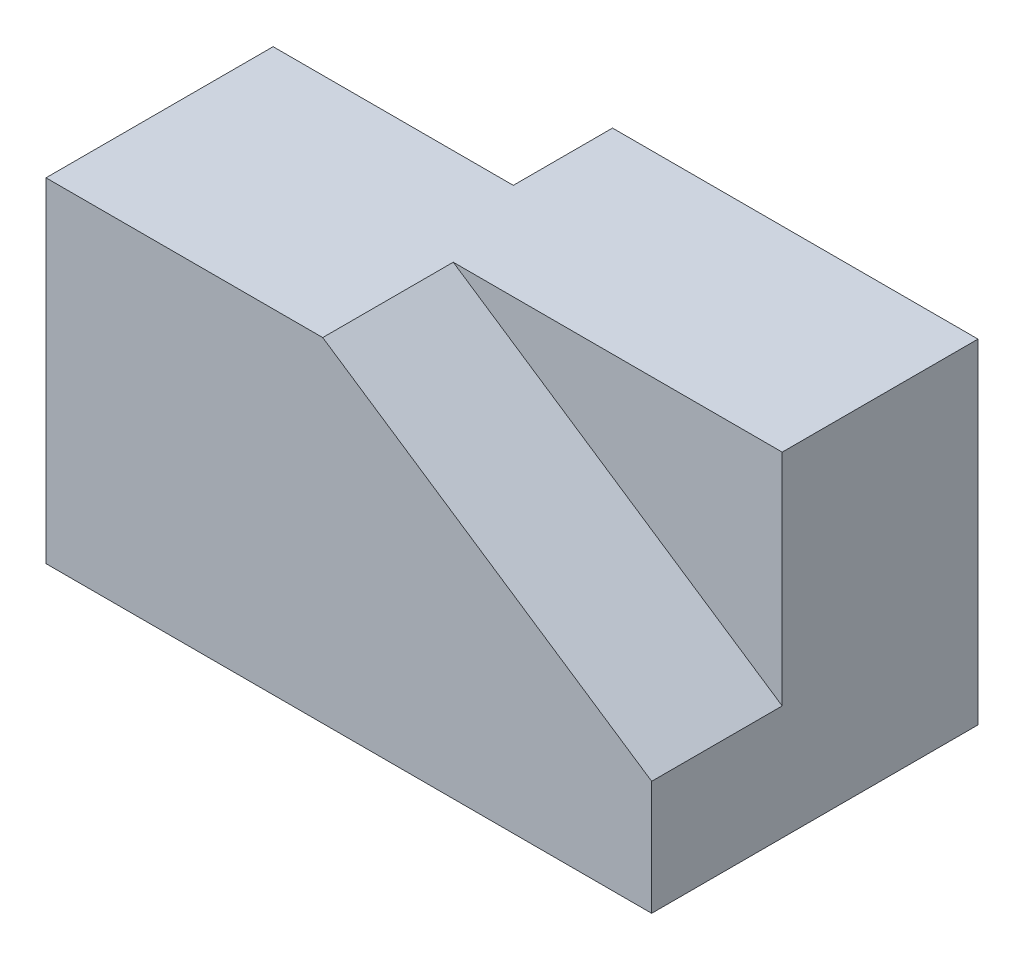
SolidWorks part; units mm, degrees
ref_plane "Front Plane" through (0, 0, 0) normal (0, 0, 1) x (1, 0, 0)
ref_plane "Top Plane" through (0, 0, 0) normal (0, 1, 0) x (1, 0, 0)
ref_plane "Right Plane" through (0, 0, 0) normal (1, 0, 0) x (0, 0, -1)
sketch "Sketch1" plane through (0, 0, 0) normal (0, 1, 0) x (1, 0, 0)
  line L1 (0, 0) -> (58.928, 0)
  line L2 (0, 0) -> (0, 31.75)
  line L3 (0, 31.75) -> (58.928, 31.75)
  line L4 (58.928, 0) -> (58.928, 31.75)
  dimension "D1" = 58.928
  dimension "D2" = 31.75
extrude "Boss-Extrude1" add sketch "Sketch1" along normal blind 32.512
sketch "Sketch3" plane through (0, 0, 0) normal (0, 0, 1) x (1, 0, 0)
  line L0 (26.924, 32.512) -> (58.928, 11.1252)
  line L1 (0, 32.512) -> (58.928, 32.512) construction
  line L3 (58.928, 11.1252) -> (58.928, 32.512)
  line L4 (58.928, 32.512) -> (26.924, 32.512)
  line L5 (0, 32.512) -> (26.924, 32.512) construction
  line L6 (58.928, 11.1252) -> (58.928, 0) construction
  line L7 (58.928, 32.512) -> (58.928, 0) construction
  dimension "D1" = 26.924
  dimension "D2" = 11.1252
extrude "Cut-Extrude1" cut sketch "Sketch3" against normal blind 12.7
sketch "Sketch4" plane through (0, 32.512, 0) normal (0, 1, 0) x (1, 0, 0)
  line L1 (0, 31.75) -> (23.368, 31.75)
  line L2 (0, 31.75) -> (0, 22.098)
  line L3 (0, 22.098) -> (23.368, 22.098)
  line L4 (23.368, 31.75) -> (23.368, 22.098)
  dimension "D1" = 23.368
  dimension "D2" = 9.652
extrude "Cut-Extrude2" cut sketch "Sketch4" against normal blind 11.176
